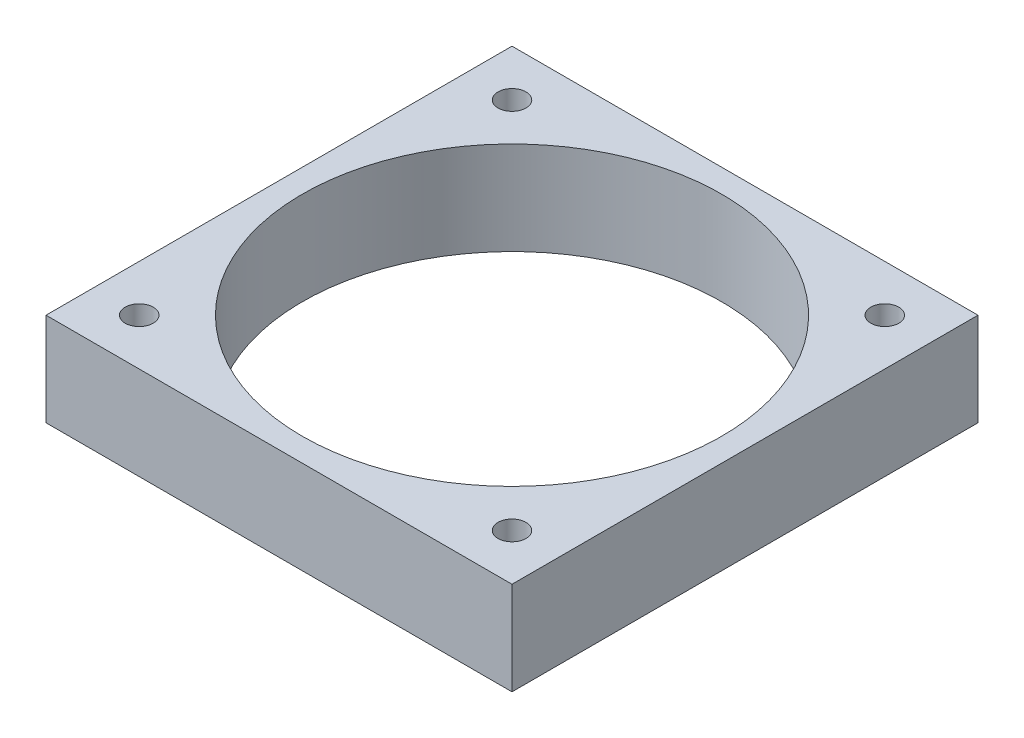
SolidWorks part; units mm, degrees
ref_plane "前视基准面" through (0, 0, 0) normal (0, 0, 1) x (1, 0, 0)
ref_plane "上视基准面" through (0, 0, 0) normal (0, 1, 0) x (1, 0, 0)
ref_plane "右视基准面" through (0, 0, 0) normal (1, 0, 0) x (0, 0, -1)
sketch "草图1" plane through (0, 0, 0) normal (0, 1, 0) x (1, 0, 0)
  line L1 (25, 25) -> (-25, 25)
  line L2 (25, 25) -> (25, -25)
  line L3 (25, -25) -> (-25, -25)
  line L4 (-25, 25) -> (-25, -25)
  line L5 (25, 25) -> (-25, -25) construction
  line L6 (25, -25) -> (-25, 25) construction
  line L7 (20, 20) -> (-20, 20) construction
  line L8 (20, 20) -> (20, -20) construction
  line L9 (20, -20) -> (-20, -20) construction
  line L10 (-20, 20) -> (-20, -20) construction
  line L11 (20, 20) -> (-20, -20) construction
  line L12 (20, -20) -> (-20, 20) construction
  circle A0 centre (-20, 20) radius 1.5
  circle A1 centre (20, 20) radius 1.5
  circle A2 centre (-20, -20) radius 1.5
  circle A3 centre (20, -20) radius 1.5
  circle A4 centre (0, 0) radius 22.5
  point P0 (0, 0)
  point P5 (0, 0)
extrude "凸台-拉伸1" add sketch "草图1" along normal blind 10 contours A4 L4 L3 A2 | A4 L1 L4 A0 | A4 L2 L1 A1 | A4 L3 L2 A3
